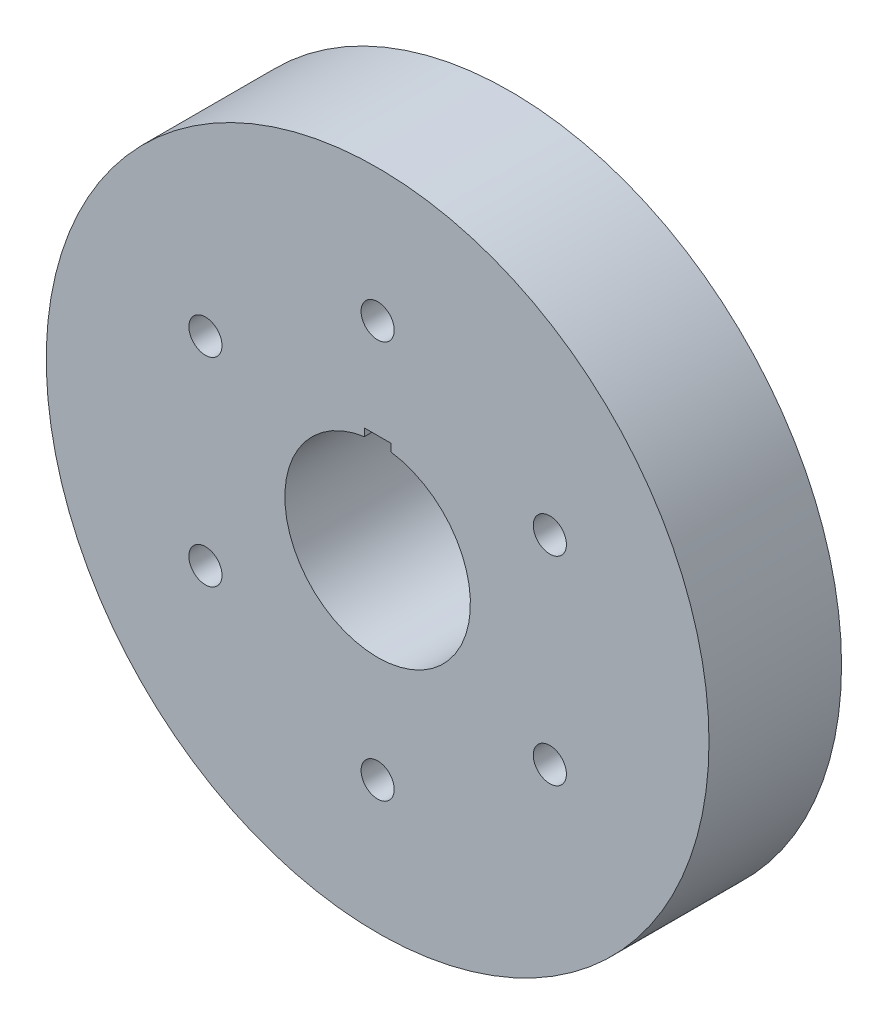
SolidWorks part; units mm, degrees
material "BUTYL"
ref_plane "Front Plane" through (0, 0, 0) normal (0, 0, 1) x (1, 0, 0)
ref_plane "Top Plane" through (0, 0, 0) normal (0, 1, 0) x (1, 0, 0)
ref_plane "Right Plane" through (0, 0, 0) normal (1, 0, 0) x (0, 0, -1)
sketch "Sketch1" plane through (0, 0, 0) normal (0, 0, 1) x (1, 0, 0)
  line L0 (-2, 13.8564) -> (-2, 15)
  line L1 (-2, 15) -> (2, 15)
  line L2 (2, 15) -> (2, 13.8564)
  circle A0 centre (0, 0) radius 50
  arc A1 (-2, 13.8564) -> (2, 13.8564) centre (0, 0) ccw
  dimension "D1" = 100
  dimension "D2" = 28
  dimension "D3" = 2
  dimension "D4" = 2
  dimension "D5" = 15
extrude "Boss-Extrude1" add sketch "Sketch1" along normal blind 20
sketch "Sketch2" plane through (0, 0, 20) normal (0, 0, 1) x (1, 0, 0)
  circle A0 centre (0, -30) radius 2.5
  circle A1 centre (0, 0) radius 50 construction
  circle A2 centre (-25.9808, -15) radius 2.5
  circle A3 centre (-25.9808, 15) radius 2.5
  circle A4 centre (0, 30) radius 2.5
  circle A5 centre (25.9808, 15) radius 2.5
  circle A6 centre (25.9808, -15) radius 2.5
  point P16 (0, 0)
  dimension "D1" = 5
  dimension "D2" = 30
  dimension "D3" = 6
extrude "Cut-Extrude1" cut sketch "Sketch2" against normal through all
